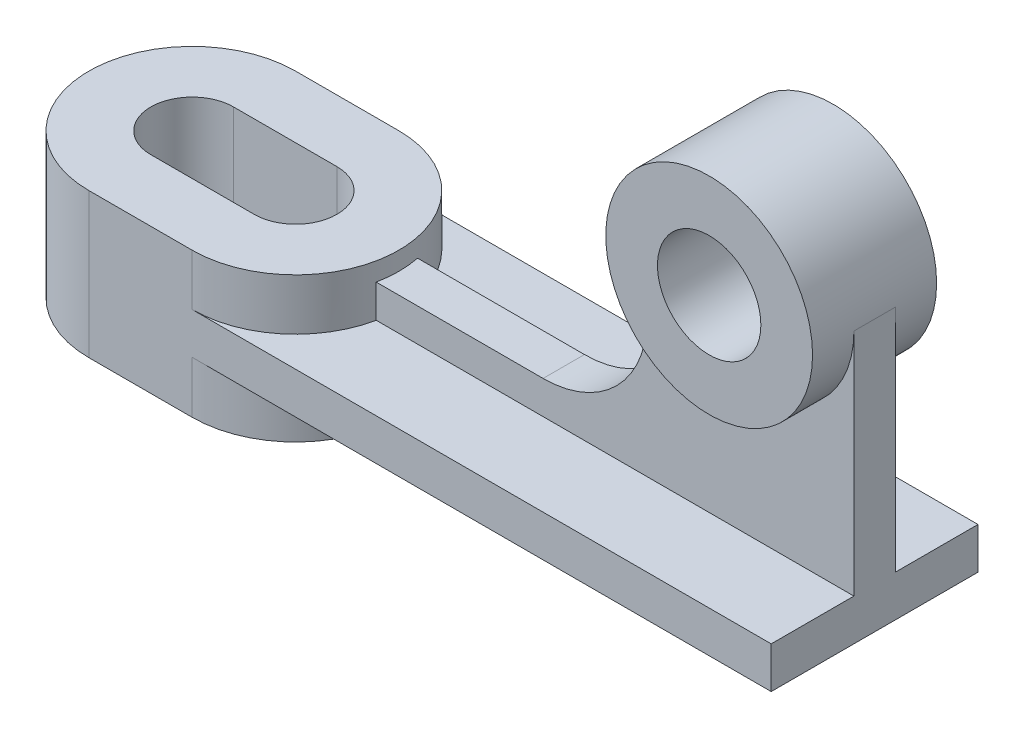
SolidWorks part; units mm, degrees
ref_plane "Front Plane" through (0, 0, 0) normal (0, 0, 1) x (1, 0, 0)
ref_plane "Top Plane" through (0, 0, 0) normal (0, 1, 0) x (1, 0, 0)
ref_plane "Right Plane" through (0, 0, 0) normal (1, 0, 0) x (0, 0, -1)
sketch "Sketch1" plane through (0, 0, 0) normal (0, 1, 0) x (1, 0, 0)
  line L0 (-12.5, 0) -> (12.5, 0) construction
  line L1 (-12.5, 10) -> (12.5, 10)
  line L2 (-12.5, -10) -> (12.5, -10)
  line L3 (-12.5, 0) -> (12.5, 0) construction
  line L4 (-12.5, 25) -> (12.5, 25)
  line L5 (-12.5, -25) -> (12.5, -25)
  arc A0 (-12.5, 10) -> (-12.5, -10) centre (-12.5, 0) ccw
  arc A1 (12.5, -10) -> (12.5, 10) centre (12.5, 0) ccw
  arc A2 (-12.5, 25) -> (-12.5, -25) centre (-12.5, 0) ccw
  arc A3 (12.5, -25) -> (12.5, 25) centre (12.5, 0) ccw
  point P2 (0, 0)
  point P10 (0, 0)
  dimension "D1" = 10
  dimension "D2" = 25
  dimension "D3" = 25
extrude "Boss-Extrude1" add sketch "Sketch1" along normal blind 35
sketch "Sketch2" plane through (0, 0, 0) normal (1, 0, 0) x (0, 0, -1)
  line L0 (0, 41.3884) -> (0, -6.2475) construction
  line L1 (25, 35) -> (25, 0) construction
  line L2 (-25, 22.5705) -> (25, 22.5705)
  line L3 (-25, 22.5705) -> (-25, 12.5705)
  line L4 (-25, 12.5705) -> (25, 12.5705)
  line L5 (25, 22.5705) -> (25, 12.5705)
  line L6 (-25, 22.5705) -> (25, 12.5705) construction
  line L7 (-25, 12.5705) -> (25, 22.5705) construction
  point P3 (0, 17.5705)
  dimension "D1" = 10
extrude "Boss-Extrude2" add sketch "Sketch2" against normal up to surface (140 mm away) from offset 152.5
sketch "Sketch3" plane through (0, 0, 0) normal (0, 0, 1) x (1, 0, 0)
  line L0 (12.5, 22.5705) -> (152.5, 22.5705) construction
  circle A0 centre (127.5, 78.0705) radius 25
  circle A1 centre (127.5, 78.0705) radius 12.5
  point P6 (115.7041, 31.8186)
  dimension "D1" = 50
  dimension "D2" = 25
  dimension "D3" = 25
  dimension "D4" = 55.5
extrude "Boss-Extrude3" add sketch "Sketch3" along normal mid plane 30 separate body
sketch "Sketch4" plane through (0, 0, 0) normal (0, 0, 1) x (1, 0, 0)
  line L0 (152.5, 78.0705) -> (152.5, 22.5705)
  line L1 (152.5, 22.5705) -> (37.5, 22.5705)
  line L2 (37.5, 22.5705) -> (37.5, 30.5705)
  line L3 (37.5, 22.5705) -> (37.5, 35) construction
  line L4 (37.5, 30.5705) -> (77.3482, 30.5705)
  line L5 (102.5, 78.0705) -> (102.5, 55.7223)
  circle A0 centre (127.5, 78.0705) radius 25 construction
  arc A1 (102.5, 55.7223) -> (77.3482, 30.5705) centre (77.3482, 55.7223) cw
  arc A2 (102.5, 78.0705) -> (152.5, 78.0705) centre (127.5, 78.0705) ccw
  dimension "D2" = 25.1518
  dimension "D1" = 8
extrude "Boss-Extrude5" add sketch "Sketch4" along normal mid plane 10 separate body
sketch "Sketch5" plane through (37.5, 0, 0) normal (-1, 0, 0) x (0, 0, 1)
  line L4 (-5, 30.5705) -> (-5, 22.5705)
  line L5 (-5, 22.5705) -> (5, 22.5705)
  line L6 (5, 22.5705) -> (5, 30.5705)
  line L7 (5, 30.5705) -> (-5, 30.5705)
  line L8 (-5, 30.5705) -> (-5, 22.5705)
  line L9 (-5, 22.5705) -> (5, 22.5705)
  line L10 (5, 22.5705) -> (5, 30.5705)
  line L11 (5, 30.5705) -> (-5, 30.5705)
  dimension "D1" = 0
extrude "Boss-Extrude6" add sketch "Sketch5" along normal up to next
